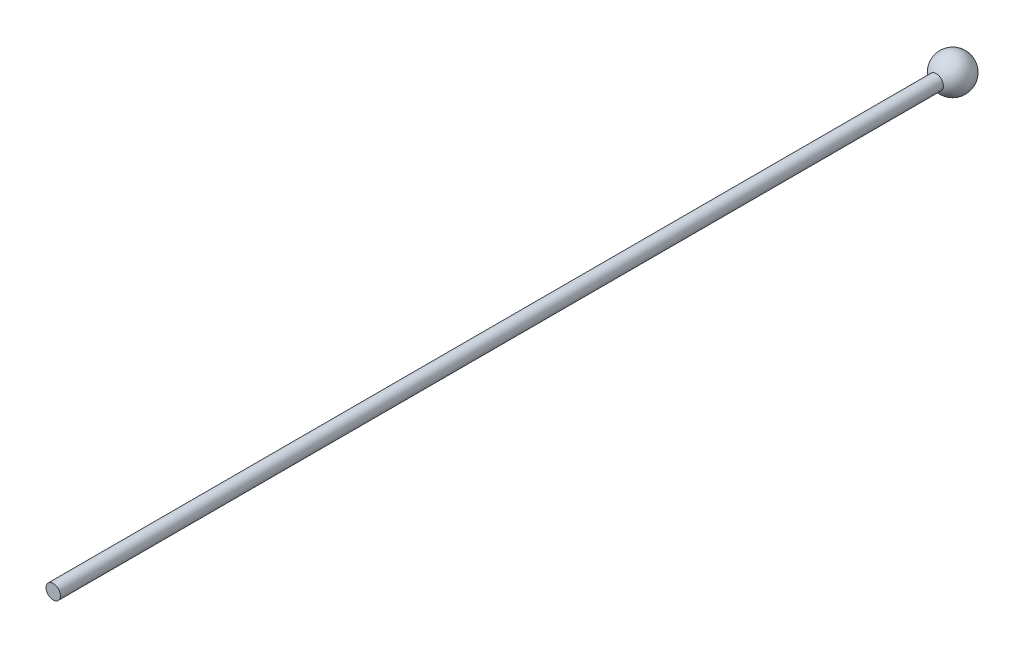
SolidWorks part; units mm, degrees
ref_plane "Front Plane" through (0, 0, 0) normal (0, 0, 1) x (1, 0, 0)
ref_plane "Top Plane" through (0, 0, 0) normal (0, 1, 0) x (1, 0, 0)
ref_plane "Right Plane" through (0, 0, 0) normal (1, 0, 0) x (0, 0, -1)
sketch "Sketch1" plane through (0, 0, 0) normal (0, 0, 1) x (1, 0, 0)
  line L0 (-27.497, 0) -> (39.9855, 0) construction
  arc A0 (10, 0) -> (-10, 0) centre (0, 0) ccw
  dimension "D1" = 20
revolve "Revolve-Thin2" add sketch "Sketch1" angle 360 about L0 wall 2
sketch "Sketch3" plane through (0, 0, 0) normal (0, 0, 1) x (1, 0, 0)
  circle A0 centre (0, 0) radius 4
  dimension "D1" = 8
extrude "Boss-Extrude2" add sketch "Sketch3" along normal blind 500
